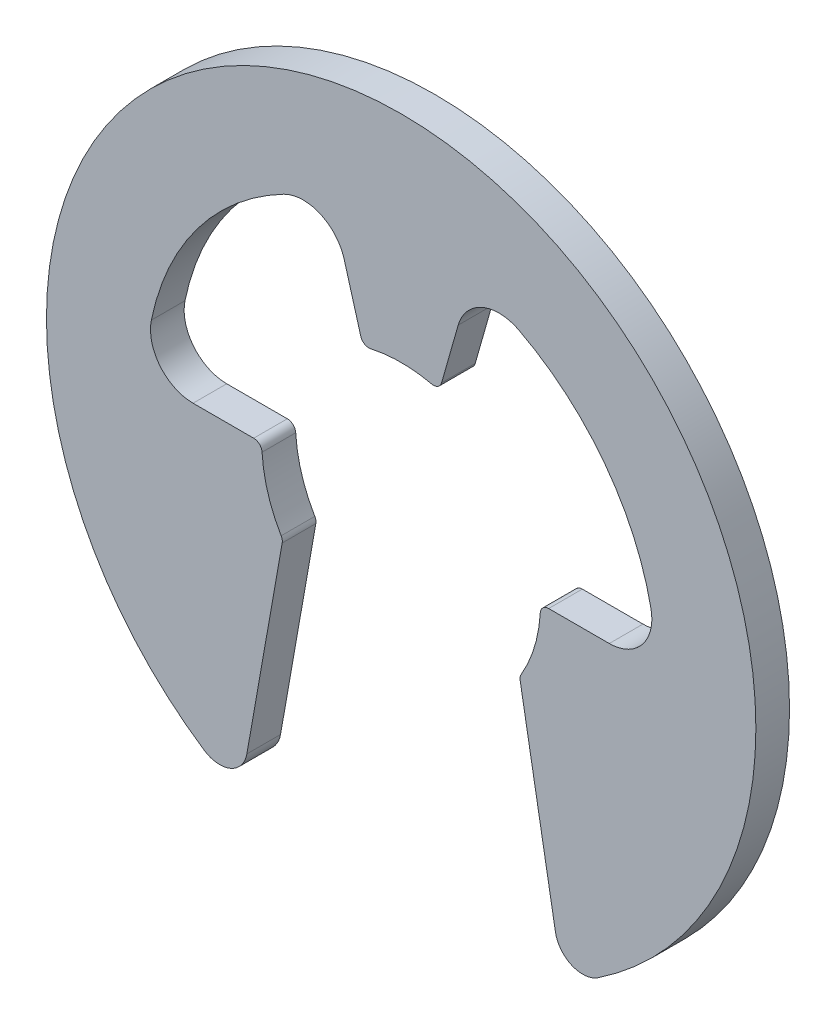
SolidWorks part; units mm, degrees
ref_plane "Front Plane" through (0, 0, 0) normal (0, 0, 1) x (1, 0, 0)
ref_plane "Top Plane" through (0, 0, 0) normal (0, 1, 0) x (1, 0, 0)
ref_plane "Right Plane" through (0, 0, 0) normal (1, 0, 0) x (0, 0, -1)
sketch "Sketch1" plane through (0, 0, 0) normal (0, 0, 1) x (1, 0, 0)
  circle A0 centre (0, 0) radius 6.6929 construction
  circle A1 centre (0, 0) radius 2.6289 construction
  point P3 (-6.6929, 0)
  dimension "Ring OD" = 13.3858
  dimension "ID" = 5.2578
sketch "Sketch2" plane through (0, 0, 0) normal (0, 1, 0) x (1, 0, 0)
  line L0 (0, -0.3175) -> (0, 0.3175) construction
  line L1 (-6.6929, -0.3175) -> (0, -0.3175) construction
  line L2 (-6.6929, -0.3175) -> (-6.6929, 0.3175) construction
  line L3 (-6.6929, 0.3175) -> (0, 0.3175) construction
  point P2 (0, 0)
  dimension "Ring Thickness" = 0.635
sketch "Sketch3" plane through (0, 0, 0) normal (0, 1, 0) x (1, 0, 0)
  line L0 (-6.6929, -0.3175) -> (-6.6929, 0.3175)
  line L1 (0, 0.3175) -> (0, -0.3175)
  line L2 (-6.6929, -0.3175) -> (0, -0.3175)
  line L3 (-6.6929, 0.3175) -> (0, 0.3175)
revolve "Revolve1" add sketch "Sketch3" angle 360 about L1
sketch "Sketch4" plane through (0, 0, 0) normal (0, 0, 1) x (1, 0, 0)
  line L0 (0.72, 2.5284) -> (1.3176, 4.6273)
  line L1 (-0.72, 2.5284) -> (-1.3176, 4.6273)
  line L2 (-2.2346, -1.3849) -> (-3.0416, -5.9618)
  line L3 (2.2346, -1.3849) -> (3.0416, -5.9618)
  line L4 (-4.8113, 0) -> (-2.6289, 0)
  line L5 (4.8113, 0) -> (2.6289, 0)
  line L6 (-6.6929, 0) -> (0, 0) construction
  line L7 (-0.72, 2.5284) -> (0.72, 2.5284) construction
  line L8 (2.6289, 0) -> (2.2346, -1.3849) construction
  circle A0 centre (0, 0) radius 6.6929 construction
  arc A1 (-3.0416, -5.9618) -> (3.0416, -5.9618) centre (0, 0) ccw
  circle A2 centre (0, 0) radius 2.6289 construction
  circle A3 centre (0, 0) radius 2.6289 construction
  arc A4 (4.8113, 0) -> (1.3176, 4.6273) centre (0, 0) ccw
  arc A5 (-0.72, 2.5284) -> (0.72, 2.5284) centre (0, 0) cw
  arc A6 (-2.6289, 0) -> (-2.2346, -1.3849) centre (0, 0) ccw
  arc A7 (2.6289, 0) -> (2.2346, -1.3849) centre (0, 0) cw
  arc A8 (-1.3176, 4.6273) -> (-4.8113, 0) centre (0, 0) ccw
  point P7 (0, 2.6289)
  dimension "D1" = 4.8113
  dimension "D5" = 20
  dimension "D2" = 4.4691
extrude "Cut-Extrude1" cut sketch "Sketch4" against normal through all both and the other way through all
fillet "Fillet1" radius 0.8031 4 edges at (4.8113, 0, 0) (1.3176, 4.6273, 0) (-1.3176, 4.6273, 0) (-4.8113, 0, 0)
fillet "Fillet2" radius 0.522 2 edges at (3.0416, -5.9618, 0) (-3.0416, -5.9618, 0)
fillet "Fillet3" radius 0.1588 6 edges at (2.2346, -1.3849, 0) (2.6289, 0, 0) (0.72, 2.5284, 0) (-0.72, 2.5284, 0) (-2.2346, -1.3849, 0) (-2.6289, 0, 0)
sketch "Sketch5" plane through (0, 0, 0) normal (0, 0, 1) x (1, 0, 0)
  arc A0 (-2.6289, 0) -> (-2.2346, -1.3849) centre (0, 0) ccw construction
  point P0 (-2.5284, -0.72)
equation "\"D1@Sketch4\"=(\"Ring OD@Sketch1\"+\"ID@Sketch1\")/3.875"
equation "\"D1@Fillet1\"=\"Ring OD@Sketch1\"*.06"
equation "\"D1@Fillet2\"=\"D1@Fillet1\"*.65"
equation "\"D1@Fillet3\"=\"Ring Thickness@Sketch2\"*.25"
equation "\"D2@Sketch4\"=\"ID@Sketch1\"*.85"
